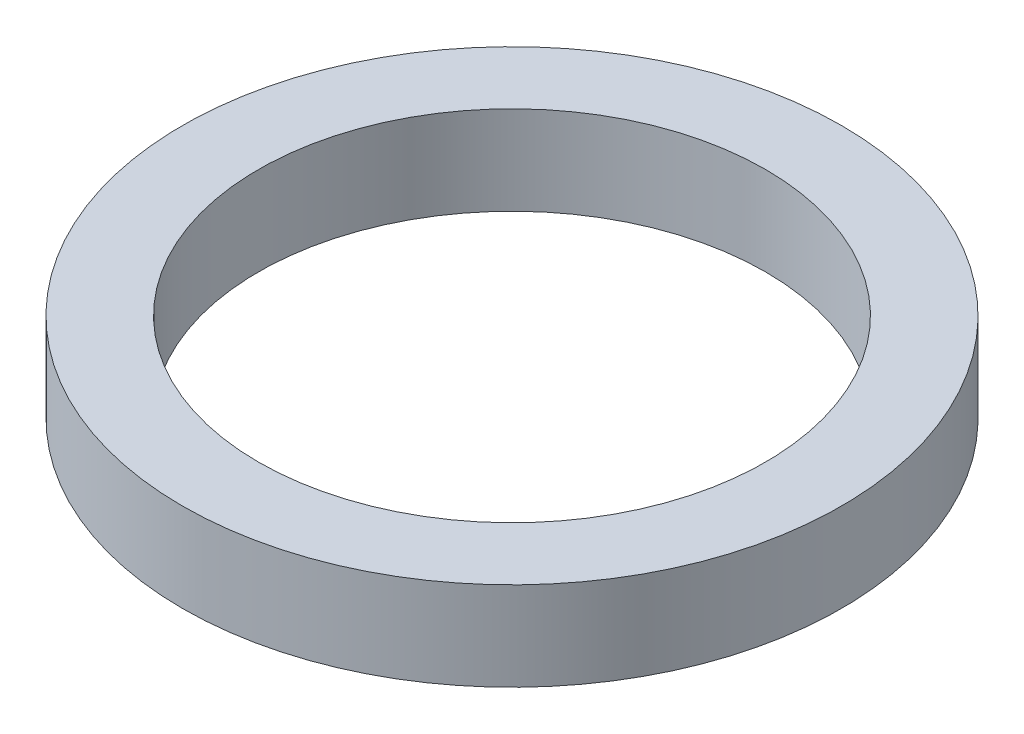
SolidWorks part; units mm, degrees
ref_plane "Ön Düzlem" through (0, 0, 0) normal (0, 0, 1) x (1, 0, 0)
ref_plane "Üst Düzlem" through (0, 0, 0) normal (0, 1, 0) x (1, 0, 0)
ref_plane "Sağ Düzlem" through (0, 0, 0) normal (1, 0, 0) x (0, 0, -1)
sketch "Sketch1" plane through (0, 0, 0) normal (0, 1, 0) x (1, 0, 0)
  circle A0 centre (0, 0) radius 20
  circle A1 centre (0, 0) radius 26
  dimension "D1" = 40
  dimension "D2" = 52
extrude "Boss-Extrude1" add sketch "Sketch1" along normal blind 7
